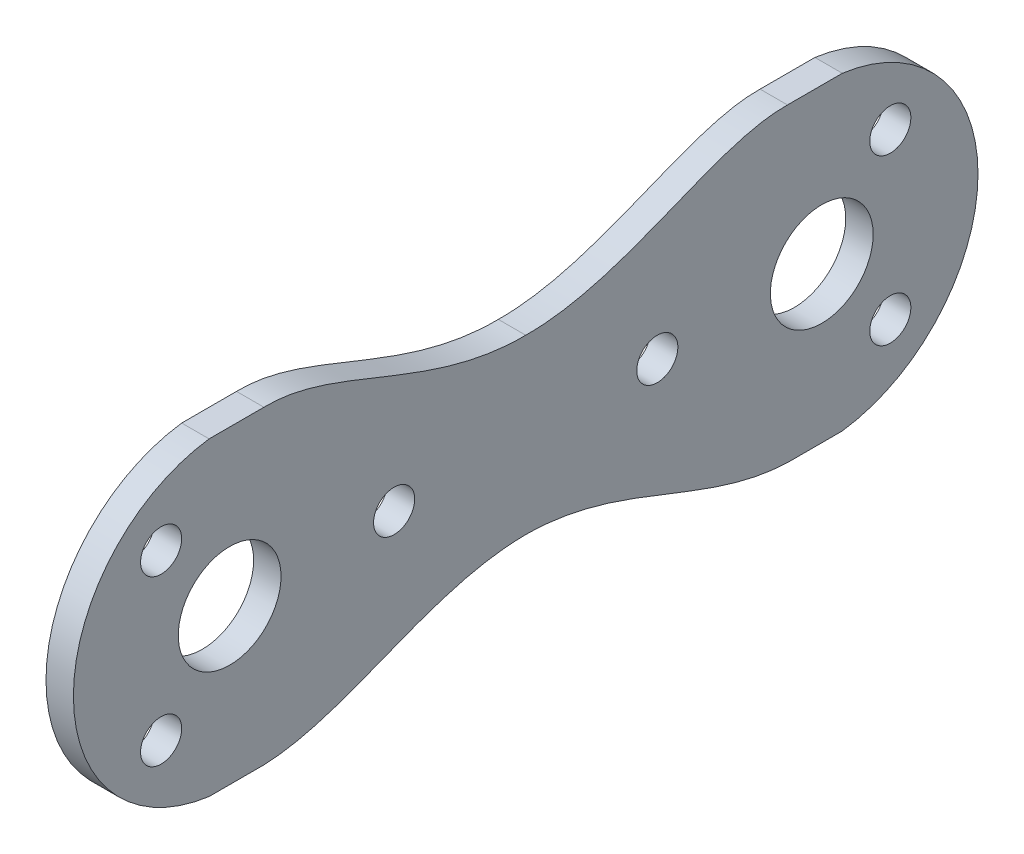
SolidWorks part; units mm, degrees
ref_plane "Piano frontale" through (0, 0, 0) normal (0, 0, 1) x (1, 0, 0)
ref_plane "Piano superiore" through (0, 0, 0) normal (0, 1, 0) x (1, 0, 0)
ref_plane "Piano destro" through (0, 0, 0) normal (1, 0, 0) x (0, 0, -1)
sketch "Schizzo1" plane through (0, 0, 0) normal (1, 0, 0) x (0, 0, -1)
  line L4 (-2.501, -10.3) -> (-2.501, -11.3)
  line L5 (-2.501, -11.3) -> (1.499, -11.3)
  line L7 (1.499, 11.3) -> (-2.501, 11.3)
  line L8 (-2.501, 11.3) -> (-2.501, 10.3)
  line L15 (-43.202, 0) -> (0, 0)
  line L30 (-2.501, 10.3) -> (-7.501, 10.3)
  line L31 (-7.501, 10.3) -> (-7.501, 6.3)
  line L32 (-7.501, 6.3) -> (-35.701, 6.3)
  line L35 (-21.601, 6.3) -> (-21.601, -6.3)
  line L36 (-35.701, -6.3) -> (-7.501, -6.3)
  line L37 (-7.501, -6.3) -> (-7.501, -10.3)
  line L38 (-7.501, -10.3) -> (-2.501, -10.3)
  line L40 (-35.701, -10.3) -> (-40.701, -10.3)
  line L41 (-35.701, -6.3) -> (-35.701, -10.3)
  line L42 (-35.701, 10.3) -> (-35.701, 6.3)
  line L43 (-40.701, 10.3) -> (-35.701, 10.3)
  line L47 (-40.701, 11.3) -> (-40.701, 10.3)
  line L48 (-44.701, 11.3) -> (-40.701, 11.3)
  line L49 (-40.701, -11.3) -> (-44.701, -11.3)
  line L50 (-40.701, -10.3) -> (-40.701, -11.3)
  arc A11 (-44.701, 11.3) -> (-44.701, -11.3) centre (-43.202, 0) ccw
  arc A14 (1.499, 11.3) -> (1.499, -11.3) centre (0, 0) cw
  circle A16 centre (-48.202, 6) radius 1.5
  circle A17 centre (-48.202, -6) radius 1.5
  circle A18 centre (-31.202, 0) radius 1.5
  circle A19 centre (-12, 0) radius 1.5
  circle A20 centre (5, 6) radius 1.5
  circle A21 centre (5, -6) radius 1.5
  circle A22 centre (-43.202, 0) radius 3.75
  circle A23 centre (0, 0) radius 3.75
  spline S0 degree 3 poles (-2.501, 11.3) (-7.8399, 11.4296) (-14.3518, 6.2167) (-21.601, 6.3) knots 0 0 0 0 1 1 1 1
  spline S1 degree 3 poles (-2.501, -11.3) (-8.7462, -11.0636) (-14.4327, -6.3399) (-21.601, -6.3) knots 0 0 0 0 1 1 1 1
  spline S2 degree 3 poles (-40.701, -11.3) (-34.4558, -11.0636) (-28.7694, -6.3399) (-21.601, -6.3) knots 0 0 0 0 1 1 1 1
  spline S3 degree 3 poles (-40.701, 11.3) (-35.3621, 11.4296) (-28.8502, 6.2167) (-21.601, 6.3) knots 0 0 0 0 1 1 1 1
  point P17 (11.399, 0)
  point P41 (-21.601, 0)
  dimension "D7" = 11.399
  dimension "D12" = 7.5
  dimension "D14" = 3
  dimension "D15" = 3
  dimension "D16" = 3
  dimension "D17" = 3
  dimension "D18" = 3
  dimension "D19" = 3
  dimension "D8" = 7.5
  dimension "D1" = 33
  dimension "D2" = 22.6
  dimension "D3" = 11.3
  dimension "D4" = 1
  dimension "D5" = 1
  dimension "D6" = 4
  dimension "D9" = 5
  dimension "D10" = 4
  dimension "D11" = 4
  dimension "D20" = 5
  dimension "D21" = 12
  dimension "D22" = 6
  dimension "D23" = 12
  dimension "D24" = 12
  dimension "D25" = 5
extrude "Estrusione-Estrusione1" add sketch "Schizzo1" along normal blind 2
